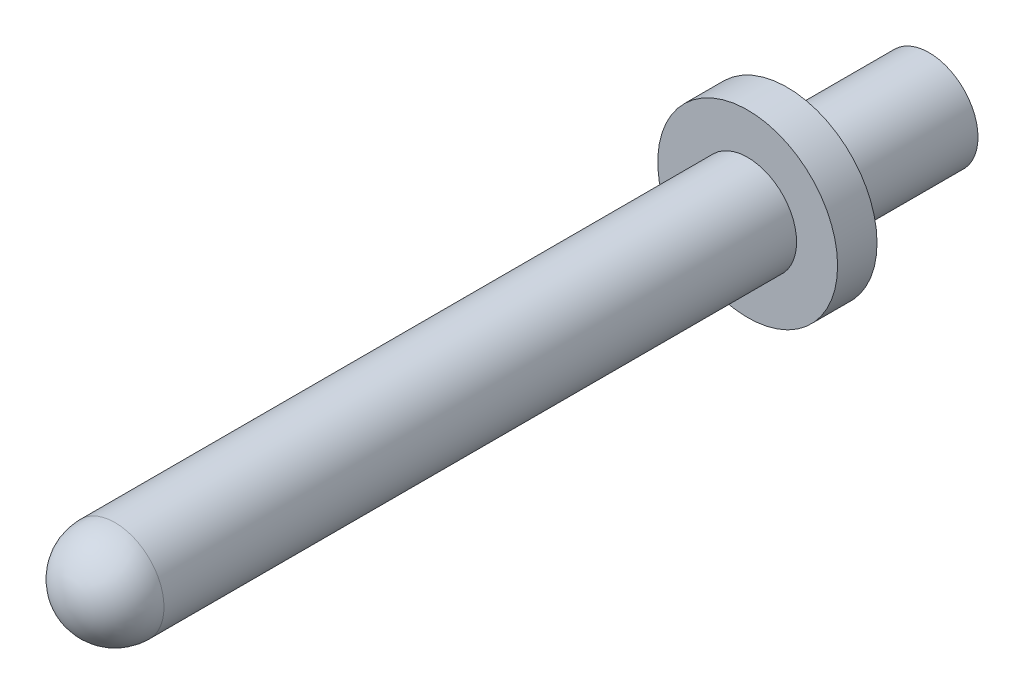
SolidWorks part; units mm, degrees
ref_plane "Front Plane" through (0, 0, 0) normal (0, 0, 1) x (1, 0, 0)
ref_plane "Top Plane" through (0, 0, 0) normal (0, 1, 0) x (1, 0, 0)
ref_plane "Right Plane" through (0, 0, 0) normal (1, 0, 0) x (0, 0, -1)
sketch "Sketch1" plane through (0, 0, 0) normal (0, 1, 0) x (1, 0, 0)
  line L0 (0.5461, 11.6078) -> (0, 11.2903)
  line L1 (0, 0) -> (0.7874, 0)
  line L2 (0, 0) -> (0, 10.9728)
  line L3 (0, 10.9728) -> (0.7874, 10.9728)
  line L4 (0.7874, 0) -> (0.7874, 10.9728)
  line L5 (0, 10.9728) -> (1.4478, 10.9728)
  line L6 (0, 10.9728) -> (0, 11.6078)
  line L7 (0, 11.6078) -> (1.4478, 11.6078)
  line L8 (1.4478, 10.9728) -> (1.4478, 11.6078)
  line L9 (0.5461, 11.6078) -> (0.7874, 11.6078)
  line L10 (0.5461, 11.6078) -> (0.5461, 13.8938)
  line L11 (0.5461, 13.8938) -> (0.7874, 13.8938)
  line L12 (0.7874, 11.6078) -> (0.7874, 13.8938)
  circle A0 centre (0, 0.7874) radius 0.7874
  dimension "D1" = 10.9728
  dimension "D2" = 0.7874
  dimension "D3" = 0.635
  dimension "D4" = 0.5461
  dimension "D5" = 0.7874
  dimension "D6" = 2.286
  dimension "D7" = 1.4478
  dimension "D8" = 0.3175
revolve "Revolve1" add sketch "Sketch1" angle 360 about L2
